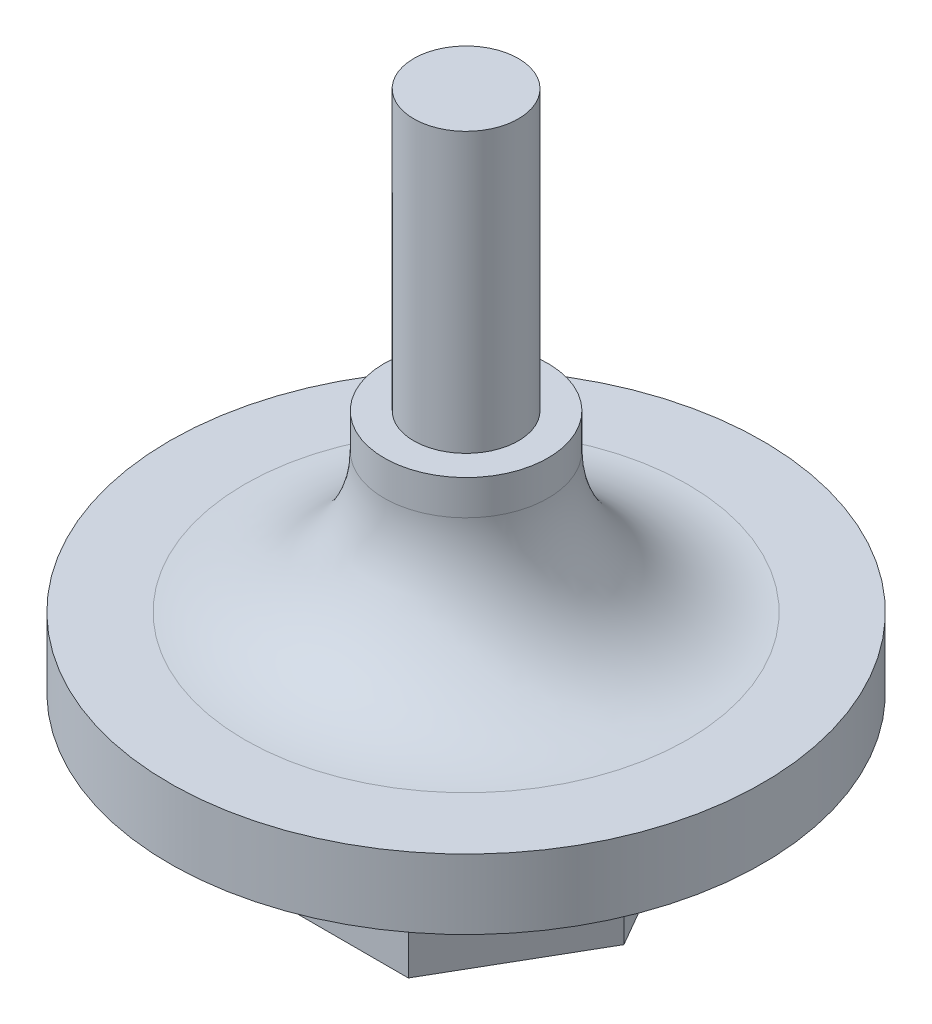
SolidWorks part; units mm, degrees
material "AISI 304"
ref_plane "Front Plane" through (0, 0, 0) normal (0, 0, 1) x (1, 0, 0)
ref_plane "Top Plane" through (0, 0, 0) normal (0, 1, 0) x (1, 0, 0)
ref_plane "Right Plane" through (0, 0, 0) normal (1, 0, 0) x (0, 0, -1)
sketch "Sketch1" plane through (0, 0, 0) normal (0, 0, 1) x (1, 0, 0)
  line L0 (0, 0) -> (13.5, 0)
  line L1 (13.5, 0) -> (13.5, 3.175)
  line L2 (13.5, 3.175) -> (10.08, 3.175)
  line L3 (3.73, 9.525) -> (3.73, 11.1125)
  line L4 (3.73, 11.1125) -> (2.3813, 11.1125)
  line L5 (2.3813, 11.1125) -> (2.3813, 23.8125)
  line L6 (2.3813, 23.8125) -> (0, 23.8125)
  line L7 (0, 23.8125) -> (0, 0) construction
  line L8 (0, 0) -> (0, 23.8125)
  arc A1 (10.08, 3.175) -> (3.73, 9.525) centre (10.08, 9.525) cw
  dimension "D6" = 6.35
  dimension "D1" = 4.7625
  dimension "D2" = 7.9375
  dimension "D3" = 3.175
  dimension "D4" = 27
  dimension "D5" = 3.73
  dimension "D7" = 12.7
revolve "Revolve1" add sketch "Sketch1" angle 360 about L7
sketch "Sketch2" plane through (0, 0, 0) normal (0, -1, 0) x (1, 0, 0)
  line L1 (7.1857, 0) -> (3.5929, 6.223)
  line L2 (3.5929, 6.223) -> (-3.5929, 6.223)
  line L3 (-3.5929, 6.223) -> (-7.1857, 0)
  line L4 (-7.1857, 0) -> (-3.5929, -6.223)
  line L5 (-3.5929, -6.223) -> (3.5929, -6.223)
  line L6 (3.5929, -6.223) -> (7.1857, 0)
  circle A0 centre (0, 0) radius 6.223 construction
  dimension "D1" = 12.446
extrude "Boss-Extrude1" add sketch "Sketch2" along normal blind 6.35
